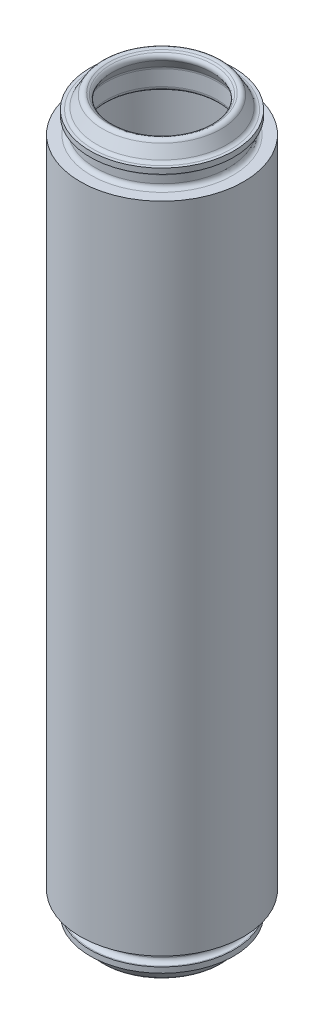
SolidWorks part; units mm, degrees
ref_plane "Front Plane" through (0, 0, 0) normal (0, 0, 1) x (1, 0, 0)
ref_plane "Top Plane" through (0, 0, 0) normal (0, 1, 0) x (1, 0, 0)
ref_plane "Right Plane" through (0, 0, 0) normal (1, 0, 0) x (0, 0, -1)
sketch "Sketch1" plane through (0, 0, 0) normal (0, 1, 0) x (1, 0, 0)
  circle A0 centre (0, 0) radius 7.5
  dimension "D1" = 15
extrude "Boss-Extrude1" add sketch "Sketch1" along normal blind 30
sketch "Sketch2" plane through (0, 30, 0) normal (0, 1, 0) x (1, 0, 0)
  circle A0 centre (0, 0) radius 6.5
  circle A1 centre (0, 0) radius 7.5
  circle A2 centre (0, 0) radius 7.5
  dimension "D1" = 0
  dimension "D2" = 1
extrude "Cut-Extrude1" cut sketch "Sketch2" against normal blind 8.5 contours A0
ref_axis "Axis1" through (0, 21.5, 0) along (0, 1, 0)
sketch "Sketch3" plane through (0, 0, 0) normal (0, 0, 1) x (1, 0, 0)
  line L0 (-7, 30) -> (-6.5, 30)
  line L1 (7.5, 30) -> (-7.5, 30) construction
  line L2 (-6.1, 30.4) -> (-6.1, 31.1)
  line L3 (-6.5, 31.5) -> (-6.6, 31.5)
  line L4 (-6.6, 31.5) -> (-6.6, 32)
  line L5 (-6.6, 32) -> (-6.3309, 32)
  line L6 (-5.9845, 32.2) -> (-5.434, 33.1536)
  line L7 (-4.8876, 33.3) -> (-4.7144, 33.2)
  line L8 (-6.5, 30) -> (-6.5, 21.5) construction
  line L9 (-4.5679, 32.6536) -> (-5.0464, 31.8249)
  line L10 (-5.1, 31.6249) -> (-5.1, 30.2058)
  line L11 (-5.2675, 29.8804) -> (-6.5, 29)
  line L12 (-6.5, 29) -> (-7, 29)
  line L13 (-7, 29) -> (-7, 30)
  line L14 (-7.5, 30) -> (-6.5, 30) construction
  line L15 (6.5, 30) -> (-6.5, 30) construction
  arc A0 (-6.3309, 32) -> (-5.9845, 32.2) centre (-6.3309, 32.4) ccw
  arc A1 (-6.1, 31.1) -> (-6.5, 31.5) centre (-6.5, 31.1) ccw
  arc A2 (-6.5, 30) -> (-6.1, 30.4) centre (-6.5, 30.4) ccw
  arc A3 (-5.1, 30.2058) -> (-5.2675, 29.8804) centre (-5.5, 30.2058) cw
  arc A4 (-5.0464, 31.8249) -> (-5.1, 31.6249) centre (-4.7, 31.6249) ccw
  arc A5 (-5.434, 33.1536) -> (-4.8876, 33.3) centre (-5.0876, 32.9536) cw
  arc A6 (-4.7144, 33.2) -> (-4.5679, 32.6536) centre (-4.9144, 32.8536) cw
  point P29 (-6.1, 32)
  point P32 (-6.1, 31.5)
  point P35 (-6.1, 30)
  point P38 (-5.1, 30)
  point P43 (-5.234, 33.5)
  point P46 (-4.3679, 33)
  dimension "D10" = 0.4
  dimension "D1" = 1.5
  dimension "D2" = 0.1
  dimension "D3" = 0.5
  dimension "D4" = 0.5
  dimension "D5" = 1
  dimension "D6" = 60
  dimension "D7" = 1
  dimension "D8" = 1
  dimension "D9" = 3.5
revolve "Revolve1" add sketch "Sketch3" angle 360 about axis through (0, 21.5, 0) along (0, 1, 0)
mirror "Mirror1" about plane through (0, 0, 0) normal (0, 1, 0) of "Cut-Extrude1", "Revolve1", "Boss-Extrude1"
